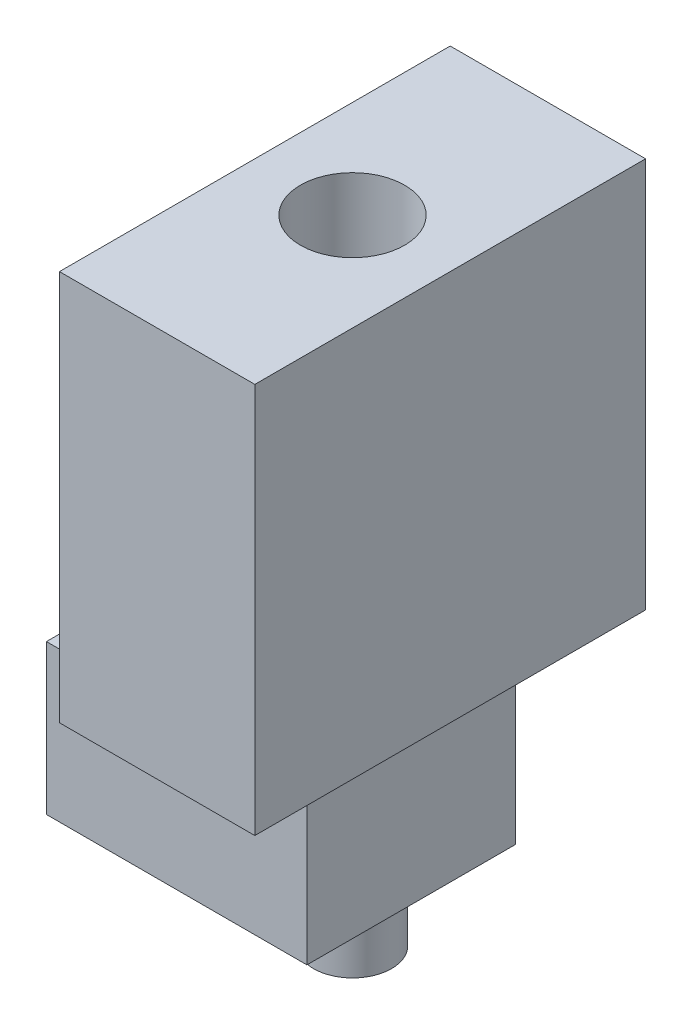
SolidWorks part; units mm, degrees
ref_plane "Спереди" through (0, 0, 0) normal (0, 0, 1) x (1, 0, 0)
ref_plane "Сверху" through (0, 0, 0) normal (0, 1, 0) x (1, 0, 0)
ref_plane "Справа" through (0, 0, 0) normal (1, 0, 0) x (0, 0, -1)
sketch "Эскиз1" plane through (0, 0, 0) normal (1, 0, 0) x (0, 0, -1)
  line L1 (0, 0) -> (30, 0)
  line L2 (0, 0) -> (0, 30)
  line L3 (0, 30) -> (30, 30)
  line L4 (30, 0) -> (30, 30)
  dimension "D1" = 30
  dimension "D2" = 30
extrude "Бобышка-Вытянуть1" add sketch "Эскиз1" along normal blind 15
hole_wizard "Диаметр отверстия Ø8.0 (8)1" positions "Эскиз2" profile "Эскиз3" hole size "Ø8.0" standard "ISO" end condition through all
sketch "Эскиз2" plane through (0, 30, 0) normal (0, 1, 0) x (1, 0, 0)
  line L0 (0, 30) -> (0, 0) construction
  line L1 (15, 30) -> (0, 30) construction
  point P0 (7.5, 15)
  dimension "D1" = 7.5
  dimension "D2" = 15
sketch "Эскиз3" plane through (7.5, 30, -15) normal (1, 0, 0) x (0, 0, 1)
  line L0 (0, 0) -> (0, 30)
  line L1 (0, 30) -> (4, 30)
  line L2 (4, 30) -> (4, 0)
  line L5 (4, 0) -> (0, 0)
  line L11 (0, -6.35) -> (0, 107.95) construction
  dimension "Диаметр сквозного отверстия" = 8
  dimension "Глубина сквозного отверстия" = 30
sketch "Эскиз4" plane through (0, 0, 0) normal (0, -1, 0) x (1, 0, 0)
  circle A0 centre (7.5, -15) radius 4
extrude "Бобышка-Вытянуть2" add sketch "Эскиз4" along normal blind 0.1 separate body
sketch "Эскиз5" plane through (0, -0.1, 0) normal (0, -1, 0) x (1, 0, 0)
  circle A0 centre (7.5, -15) radius 1.5
extrude "Бобышка-Вытянуть3" add sketch "Эскиз5" along normal blind 2
sketch "Эскиз6" plane through (0, -2.1, 0) normal (0, -1, 0) x (1, 0, 0)
  line L1 (-8, -7) -> (12, -7)
  line L2 (-8, -7) -> (-8, -23)
  line L3 (-8, -23) -> (12, -23)
  line L4 (12, -7) -> (12, -23)
  circle A1 centre (7.5, -15) radius 1.5 construction
  dimension "D3" = 4.5
  dimension "D1" = 20
  dimension "D2" = 16
  dimension "D4" = 8
extrude "Бобышка-Вытянуть4" add sketch "Эскиз6" along normal blind 11.5
sketch "Эскиз7" plane through (0, -13.6, 0) normal (0, -1, 0) x (1, 0, 0)
  line L0 (12, -23) -> (12, -7) construction
  circle A0 centre (7.5, -15) radius 3
  dimension "D1" = 6
  dimension "D2" = 4.5
  dimension "D3" = 8
extrude "Бобышка-Вытянуть5" add sketch "Эскиз7" along normal blind 5
